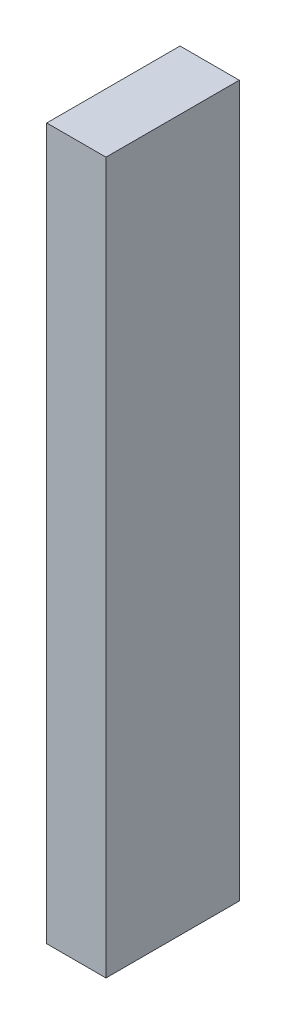
SolidWorks part; units mm, degrees
material "MDF"
ref_plane "Front Plane" through (0, 0, 0) normal (0, 0, 1) x (1, 0, 0)
ref_plane "Top Plane" through (0, 0, 0) normal (0, 1, 0) x (1, 0, 0)
ref_plane "Right Plane" through (0, 0, 0) normal (1, 0, 0) x (0, 0, -1)
sketch "Sketch1" plane through (0, 0, 0) normal (0, 0, 1) x (1, 0, 0)
  line L1 (-126.4888, -463.55) -> (-113.7888, -463.55)
  line L2 (-126.4888, -463.55) -> (-126.4888, -311.15)
  line L3 (-126.4888, -311.15) -> (-113.7888, -311.15)
  line L4 (-113.7888, -463.55) -> (-113.7888, -311.15)
  dimension "D1" = 12.7
  dimension "D2" = 152.4
extrude "Boss-Extrude1" add sketch "Sketch1" along normal up to surface (28.575 mm away)
